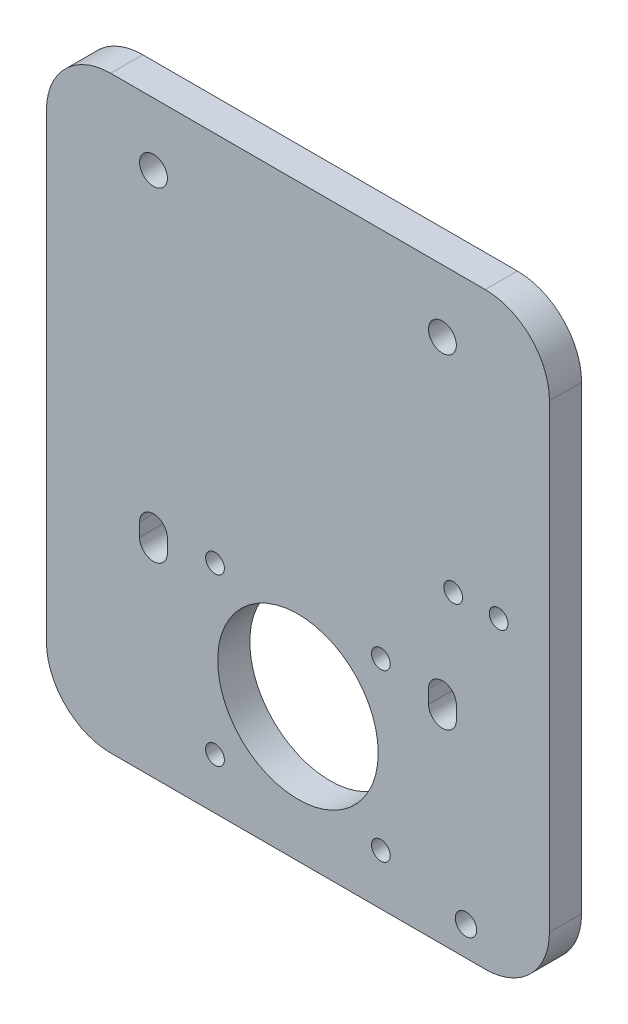
SolidWorks part; units mm, degrees
material "Acrylic (Medium-high impact)"
ref_plane "Спереди" through (0, 0, 0) normal (0, 0, 1) x (1, 0, 0)
ref_plane "Сверху" through (0, 0, 0) normal (0, 1, 0) x (1, 0, 0)
ref_plane "Справа" through (0, 0, 0) normal (1, 0, 0) x (0, 0, -1)
sketch "Model" plane through (0, 0, 0) normal (0, 0, 1) x (1, 0, 0)
  line L4 (-22.7195, 98.3) -> (-31.6357, 98.3) construction
  line L5 (-27, 102.2644) -> (-27, 93.0751) construction
  line L24 (-27, 44.8397) -> (-27, 32.6753) construction
  line L25 (-29.6, 40.1) -> (-29.6, 37.6)
  line L26 (-24.4, 37.6) -> (-24.4, 40.1)
  line L27 (-24.4, 40.1) -> (-24.4, 37.6)
  line L28 (-29.6, 37.6) -> (-29.6, 40.1)
  line L156 (-18.8648, 25) -> (20.0371, 25) construction
  line L157 (13.2088, 9.5) -> (17.9881, 9.5) construction
  line L158 (15.5, 11.4003) -> (15.5, 7.7373) construction
  line L159 (27, 44.8397) -> (27, 32.6753) construction
  line L160 (47, 98) -> (47, 12)
  line L165 (27, 102.2644) -> (27, 93.0751) construction
  line L166 (22.7195, 98.3) -> (31.6357, 98.3) construction
  line L167 (35, 0) -> (-35, 0)
  line L171 (15.5, 38.5997) -> (15.5, 42.2627) construction
  line L172 (13.2088, 40.5) -> (17.9881, 40.5) construction
  line L173 (-13.2088, 40.5) -> (-17.9881, 40.5) construction
  line L174 (-47, 12) -> (-47, 98)
  line L175 (-15.5, 38.5997) -> (-15.5, 42.2627) construction
  line L176 (-15.5, 11.4003) -> (-15.5, 7.7373) construction
  line L177 (-13.2088, 9.5) -> (-17.9881, 9.5) construction
  line L181 (-35, 110) -> (35, 110)
  line L955 (29.6, 37.6) -> (29.6, 40.1)
  line L968 (24.4, 40.1) -> (24.4, 37.6)
  line L1360 (24.4, 37.6) -> (24.4, 40.1)
  line L1373 (29.6, 40.1) -> (29.6, 37.6)
  line L1604 (0, -6.1891) -> (0, 116.9068) construction
  arc A0 (35, 110) -> (47, 98) centre (35, 98) cw
  arc A1 (47, 12) -> (35, 0) centre (35, 12) cw
  arc A2 (-47, 12) -> (-35, 0) centre (-35, 12) ccw
  arc A3 (-47, 98) -> (-35, 110) centre (-35, 98) cw
  circle A4 centre (15.5, 9.5) radius 1.75
  circle A5 centre (15.5, 40.5) radius 1.75
  circle A6 centre (-15.5, 40.5) radius 1.75
  circle A7 centre (-15.5, 9.5) radius 1.75
  circle A8 centre (0, 25) radius 15
  arc A9 (24.4, 40.1) -> (29.6, 40.1) centre (27, 40.1) cw
  arc A10 (24.4, 37.6) -> (29.6, 37.6) centre (27, 37.6) ccw
  circle A19 centre (27, 98.3) radius 2.6
  circle A22 centre (-27, 98.3) radius 2.6
  arc A29 (-24.4, 37.6) -> (-29.6, 37.6) centre (-27, 37.6) cw
  arc A30 (-24.4, 40.1) -> (-29.6, 40.1) centre (-27, 40.1) ccw
  dimension "D1" = 12
  dimension "D11" = 3.5
  dimension "D12" = 30
  dimension "D15" = 2.6
  dimension "D38" = 5.2
  dimension "D2" = 31
  dimension "D3" = 110
  dimension "D4" = 25
  dimension "D5" = 31
  dimension "D6" = 40.1
  dimension "D7" = 94
  dimension "D8" = 54
  dimension "D13" = 5.2
  dimension "D14" = 2.5
  dimension "D36" = 58.2
extrude "Base" add sketch "Model" along normal blind 6
sketch "Sketch1" plane through (0, 0, 0) normal (0, 0, -1) x (-1, 0, 0)
  line L1 (-35, 0) -> (35, 0) construction
  line L3 (-47, 98) -> (-47, 12) construction
  circle A0 centre (-29, 58) radius 1.75
  circle A1 centre (-37.5, 58) radius 1.75
  dimension "D1" = 3.5
  dimension "D3" = 9.5
  dimension "D4" = 8.5
  dimension "D5" = 58
extrude "CableChainMount" cut sketch "Sketch1" against normal blind 10
sketch "Sketch2" plane through (0, 0, 6) normal (0, 0, 1) x (1, 0, 0)
  circle A0 centre (31.3948, 5.5057) radius 2
  dimension "D1" = 4
extrude "CableTieMount" cut sketch "Sketch2" against normal through all
